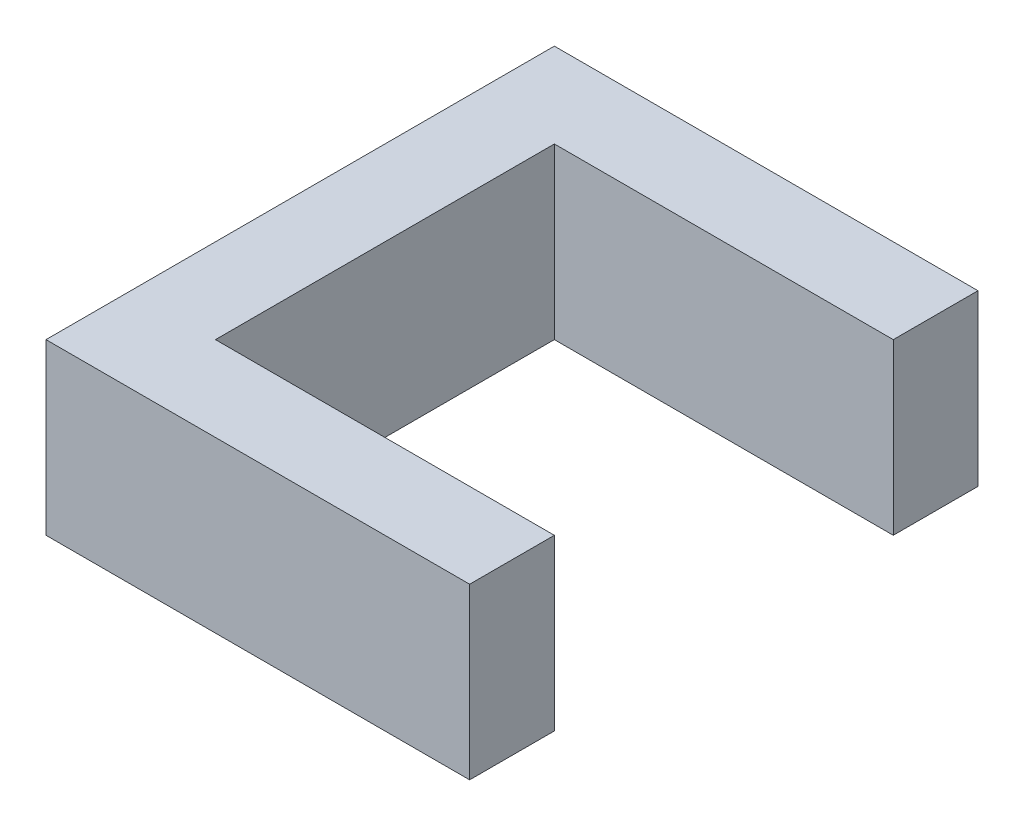
SolidWorks part; units mm, degrees
ref_plane "Přední rovina" through (0, 0, 0) normal (0, 0, 1) x (1, 0, 0)
ref_plane "Horní rovina" through (0, 0, 0) normal (0, 1, 0) x (1, 0, 0)
ref_plane "Pravá rovina" through (0, 0, 0) normal (1, 0, 0) x (0, 0, -1)
sketch "Sketch1" plane through (0, 0, 0) normal (0, 1, 0) x (1, 0, 0)
  line L0 (0, 0) -> (0, -60)
  line L1 (0, -60) -> (50, -60)
  line L2 (50, -60) -> (50, -50)
  line L3 (50, -50) -> (10, -50)
  line L4 (10, -50) -> (10, -10)
  line L5 (10, -10) -> (50, -10)
  line L6 (50, -10) -> (50, 0)
  line L7 (50, 0) -> (0, 0)
  dimension "D1" = 10
  dimension "D2" = 10
  dimension "D3" = 40
  dimension "D4" = 10
  dimension "D5" = 40
extrude "Boss-Extrude1" add sketch "Sketch1" along normal blind 20
equation "\"H\" = 40"
equation "\"D3@Sketch1\"=\"H\""
equation "\"L\"= 40"
equation "\"D5@Sketch1\"=\"L\""
